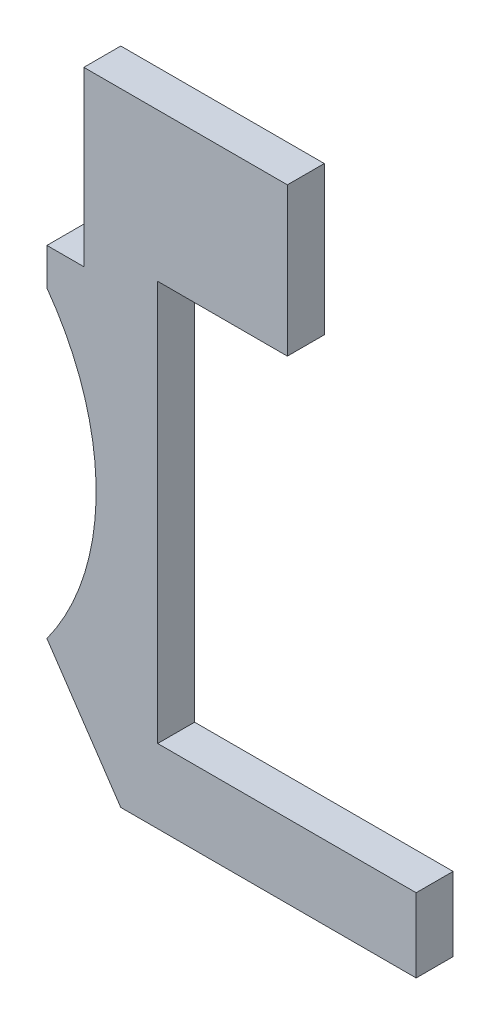
SolidWorks part; units mm, degrees
material "Balsa"
ref_plane "Plan de face" through (0, 0, 0) normal (0, 0, 1) x (1, 0, 0)
ref_plane "Plan de dessus" through (0, 0, 0) normal (0, 1, 0) x (1, 0, 0)
ref_plane "Plan de droite" through (0, 0, 0) normal (1, 0, 0) x (0, 0, -1)
sketch "Esquisse1" plane through (0, 0, 0) normal (0, 0, 1) x (1, 0, 0)
  line L0 (50, 0) -> (50, 10)
  line L1 (10, 0) -> (50, 0)
  line L2 (10, 0) -> (0, 14.8116)
  line L3 (0, 60.9124) -> (5, 60.9124)
  line L4 (50, 10) -> (15, 10)
  line L5 (15, 10) -> (15, 64.2031)
  line L6 (15, 64.2031) -> (32.5611, 64.2031)
  line L7 (5, 60.9124) -> (5, 84.2947)
  line L8 (0, 60.9124) -> (0, 55.9124)
  line L9 (5, 84.2947) -> (32.5611, 84.2947)
  line L10 (32.5611, 84.2947) -> (32.5611, 64.2031)
  arc A0 (0, 14.8116) -> (0, 55.9124) centre (-28.3316, 35.362) ccw
  dimension "D3" = 35
  dimension "D1" = 5
  dimension "D2" = 5
  dimension "D4" = 10
  dimension "D6" = 15
  dimension "D7" = 10
extrude "Boss.-Extru.1" add sketch "Esquisse1" along normal blind 5
